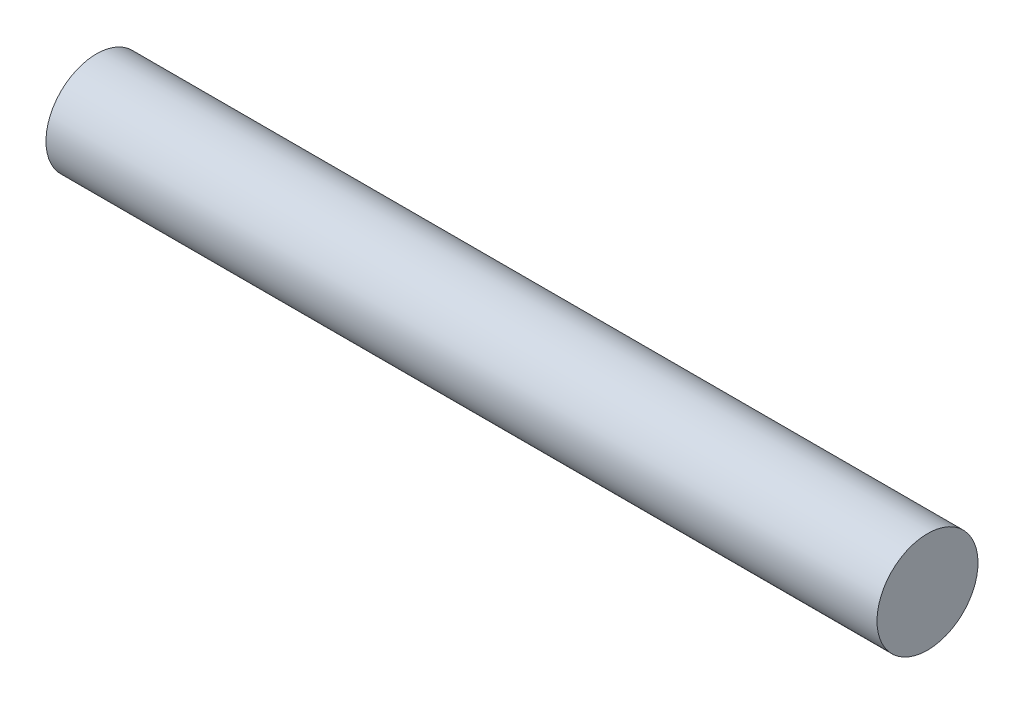
SolidWorks part; units mm, degrees
ref_plane "Front Plane" through (0, 0, 0) normal (0, 0, 1) x (1, 0, 0)
ref_plane "Top Plane" through (0, 0, 0) normal (0, 1, 0) x (1, 0, 0)
ref_plane "Right Plane" through (0, 0, 0) normal (1, 0, 0) x (0, 0, -1)
sketch "Sketch1" plane through (0, 0, 0) normal (1, 0, 0) x (0, 0, -1)
  circle A0 centre (0, 0) radius 3.57
  dimension "D1" = 7.14
extrude "Boss-Extrude1" add sketch "Sketch1" along normal up to surface (58.7248 mm away)
